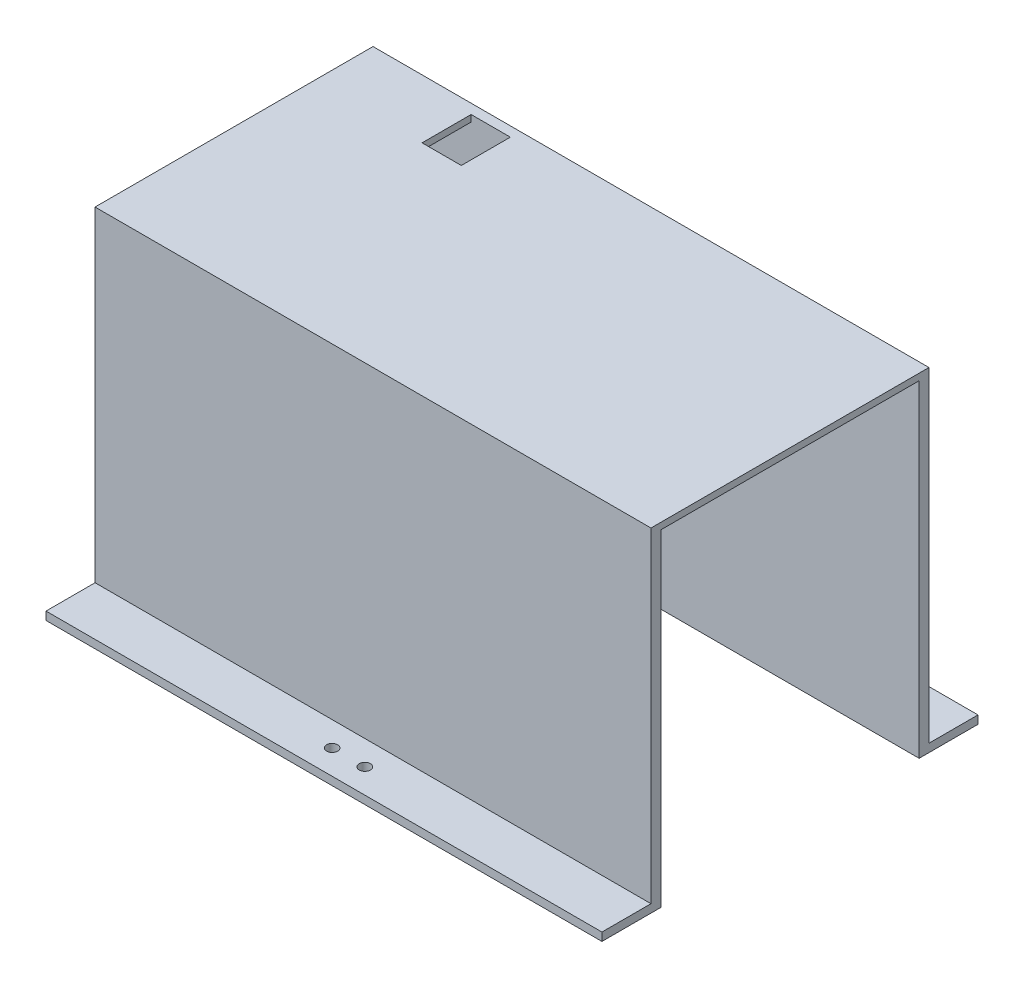
SolidWorks part; units mm, degrees
ref_plane "Front Plane" through (0, 0, 0) normal (0, 0, 1) x (1, 0, 0)
ref_plane "Top Plane" through (0, 0, 0) normal (0, 1, 0) x (1, 0, 0)
ref_plane "Right Plane" through (0, 0, 0) normal (1, 0, 0) x (0, 0, -1)
sketch "Sketch2" plane through (0, 0, 0) normal (0, 1, 0) x (1, 0, 0)
  line L1 (-74.5992, 39.4515) -> (95.4008, 39.4515)
  line L2 (-74.5992, 39.4515) -> (-74.5992, -45.5485)
  line L3 (-74.5992, -45.5485) -> (95.4008, -45.5485)
  line L4 (95.4008, 39.4515) -> (95.4008, -45.5485)
  dimension "D1" = 170
  dimension "D2" = 85
extrude "Boss-Extrude1" add sketch "Sketch2" along normal blind 2
sketch "Sketch3" plane through (0, 2, 0) normal (0, 1, 0) x (1, 0, 0)
  line L0 (-41.5992, 36.4515) -> (-41.5992, 21.4515)
  line L1 (95.4008, 39.4515) -> (-74.5992, 39.4515) construction
  line L3 (-29.5992, 36.4515) -> (-29.5992, 21.4515)
  line L4 (-74.5992, 39.4515) -> (-74.5992, -45.5485) construction
  line L5 (-41.5992, 36.4515) -> (-29.5992, 36.4515)
  line L6 (-41.5992, 21.4515) -> (-29.5992, 21.4515)
  point P14 (0, 0)
  dimension "D1" = 33
  dimension "D2" = 12
  dimension "D3" = 3
  dimension "D4" = 15
extrude "Cut-Extrude1" cut sketch "Sketch3" against normal through all
sketch "Sketch6" plane through (0, 0, 0) normal (0, -1, 0) x (1, 0, 0)
  line L0 (95.4008, 45.5485) -> (95.4008, -39.4515) construction
  line L1 (-74.5992, -39.4515) -> (95.4008, -39.4515)
  line L2 (-74.5992, -39.4515) -> (-74.5992, -36.4515)
  line L3 (-74.5992, -36.4515) -> (95.4008, -36.4515)
  line L4 (95.4008, -39.4515) -> (95.4008, -36.4515)
  line L6 (-74.5992, 45.5485) -> (95.4008, 45.5485)
  line L7 (-74.5992, 45.5485) -> (-74.5992, 42.5485)
  line L8 (-74.5992, 42.5485) -> (95.4008, 42.5485)
  line L9 (95.4008, 45.5485) -> (95.4008, 42.5485)
  dimension "D1" = 3
extrude "Boss-Extrude2" add sketch "Sketch6" along normal blind 100
sketch "Sketch7" plane through (0, 0, -39.4515) normal (0, 0, -1) x (-1, 0, 0)
  line L0 (74.5992, 2) -> (74.5992, -100) construction
  line L1 (-95.4008, -100) -> (74.5992, -100)
  line L2 (-95.4008, -100) -> (-95.4008, -97.5)
  line L3 (-95.4008, -97.5) -> (74.5992, -97.5)
  line L4 (74.5992, -100) -> (74.5992, -97.5)
  dimension "D1" = 2.5
extrude "Boss-Extrude3" add sketch "Sketch7" along normal blind 15
sketch "Sketch8" plane through (0, 0, 45.5485) normal (0, 0, 1) x (1, 0, 0)
  line L0 (95.4008, 2) -> (95.4008, -100) construction
  line L1 (-74.5992, -100) -> (95.4008, -100)
  line L2 (-74.5992, -100) -> (-74.5992, -97.5)
  line L3 (-74.5992, -97.5) -> (95.4008, -97.5)
  line L4 (95.4008, -100) -> (95.4008, -97.5)
  dimension "D1" = 2.5
extrude "Boss-Extrude4" add sketch "Sketch8" along normal blind 15
sketch "Sketch9" plane through (0, -97.5, 0) normal (0, 1, 0) x (1, 0, 0)
  line L0 (-74.5992, -60.5485) -> (-74.5992, -45.5485) construction
  line L1 (-74.5992, -45.5485) -> (95.4008, -45.5485) construction
  circle A0 centre (5.4008, -53.0485) radius 1.7
  circle A1 centre (15.4008, -53.0485) radius 1.7
  point P4 (0, 0)
  dimension "D1" = 10
  dimension "D2" = 80
  dimension "D3" = 7.5
extrude "Cut-Extrude3" cut sketch "Sketch9" against normal through all
sketch "Sketch11" plane through (0, -97.5, 0) normal (0, 1, 0) x (1, 0, 0)
  line L0 (-74.5992, 54.4515) -> (-74.5992, 39.4515) construction
  line L1 (-74.5992, 54.4515) -> (95.4008, 54.4515) construction
  circle A0 centre (5.4008, 46.9515) radius 1.7
  circle A1 centre (15.4008, 46.9515) radius 1.7
  point P6 (0, 0)
  point P7 (0, 0)
  point P8 (15.6221, 41.1367)
  dimension "D1" = 80
  dimension "D2" = 10
  dimension "D3" = 7.5
extrude "Cut-Extrude4" cut sketch "Sketch11" against normal through all
